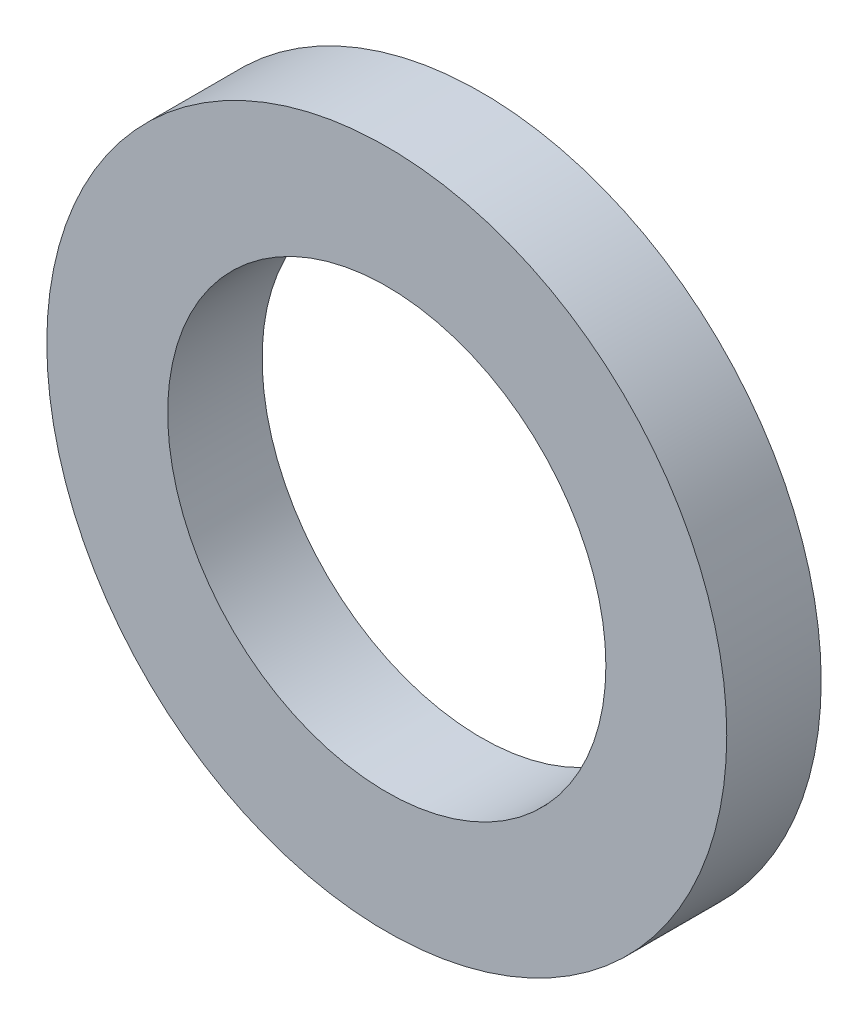
SolidWorks part; units mm, degrees
material "PE High Density Film"
ref_plane "Front Plane" through (0, 0, 0) normal (0, 0, 1) x (1, 0, 0)
ref_plane "Top Plane" through (0, 0, 0) normal (0, 1, 0) x (1, 0, 0)
ref_plane "Right Plane" through (0, 0, 0) normal (1, 0, 0) x (0, 0, -1)
sketch "Sketch1" plane through (0, 0, 0) normal (0, 0, 1) x (1, 0, 0)
  circle A0 centre (0, 0) radius 9
  circle A1 centre (0, 0) radius 5.8
  dimension "D1" = 11.6
  dimension "D2" = 18
extrude "Boss-Extrude1" add sketch "Sketch1" along normal blind 2.5
